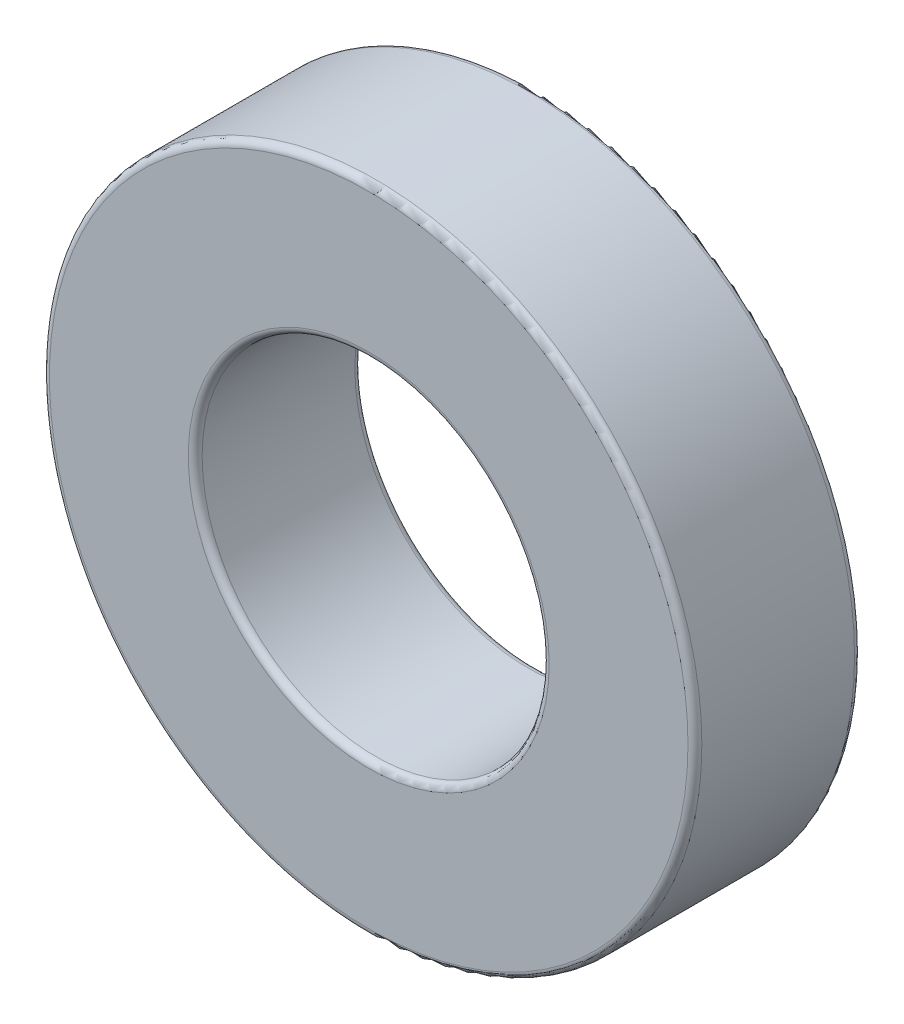
SolidWorks part; units mm, degrees
material "Alloy Steel"
ref_plane "Front Plane" through (0, 0, 0) normal (0, 0, 1) x (1, 0, 0)
ref_plane "Top Plane" through (0, 0, 0) normal (0, 1, 0) x (1, 0, 0)
ref_plane "Right Plane" through (0, 0, 0) normal (1, 0, 0) x (0, 0, -1)
sketch "Sketch1" plane through (0, 0, 0) normal (0, 0, 1) x (1, 0, 0)
  circle A0 centre (0, 0) radius 23.5
  circle A1 centre (0, 0) radius 12.5
  dimension "D1" = 47
  dimension "D2" = 25
extrude "Boss-Extrude1" add sketch "Sketch1" along normal blind 12
fillet "Fillet1" radius 0.5 2 edges at (23.5, 0, 0) (23.5, 0, 12)
fillet "Fillet2" radius 0.5 2 edges at (12.5, 0, 0) (12.5, 0, 12)
